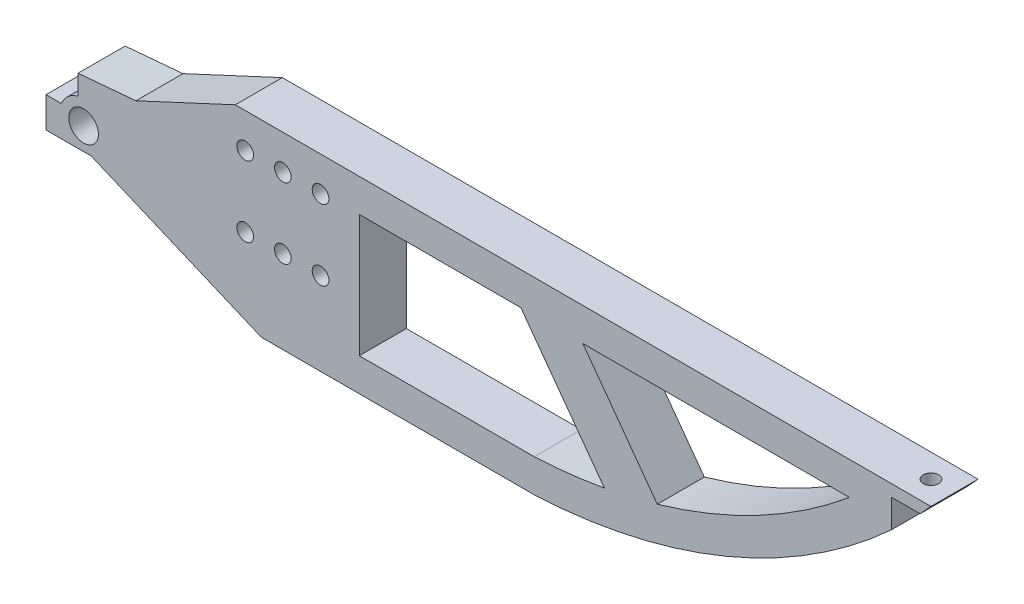
SolidWorks part; units mm, degrees
ref_plane "Front Plane" through (0, 0, 0) normal (0, 0, 1) x (1, 0, 0)
ref_plane "Top Plane" through (0, 0, 0) normal (0, 1, 0) x (1, 0, 0)
ref_plane "Right Plane" through (0, 0, 0) normal (1, 0, 0) x (0, 0, -1)
sketch "Sketch1" plane through (0, 0, 0) normal (0, 0, 1) x (1, 0, 0)
  line L1 (120.65, 25.4) -> (-120.65, 25.4)
  line L2 (120.65, 25.4) -> (120.65, -25.4)
  line L3 (120.65, -25.4) -> (-120.65, -25.4)
  line L4 (-120.65, 25.4) -> (-120.65, -25.4)
  line L5 (120.65, 25.4) -> (-120.65, -25.4) construction
  line L6 (120.65, -25.4) -> (-120.65, 25.4) construction
  point P0 (0, 0)
  dimension "D1" = 241.3
  dimension "D2" = 50.8
extrude "Boss-Extrude1" add sketch "Sketch1" along normal blind 12.7
sketch "Sketch3" plane through (0, 0, 12.7) normal (0, 0, 1) x (1, 0, 0)
  line L0 (0, 0) -> (-120.65, 0) construction
  line L1 (-120.65, 25.4) -> (-120.65, -25.4) construction
  circle A0 centre (-107.95, 0) radius 4
  dimension "D2" = 8
  dimension "D1" = 12.7
extrude "Cut-Extrude1" cut sketch "Sketch3" against normal through all
sketch "Sketch5" plane through (0, 0, 12.7) normal (0, 0, 1) x (1, 0, 0)
  line L0 (-120.65, -25.4) -> (120.65, -25.4) construction
  line L1 (-105.8942, -6.008) -> (-59.9903, -25.4)
  line L2 (-107.95, 6.35) -> (-67.0151, 25.4)
  line L3 (120.65, 25.4) -> (-120.65, 25.4) construction
  line L4 (-67.0151, 25.4) -> (-120.65, 25.4)
  line L5 (-120.65, 25.4) -> (-120.65, -25.4)
  line L6 (-120.65, -25.4) -> (-59.9903, -25.4)
  line L7 (120.65, 25.4) -> (120.65, -25.4)
  line L8 (120.65, -25.4) -> (0, -25.4)
  line L9 (-109.9582, -6.0241) -> (-105.8942, -6.008)
  line L10 (-118.0862, -6.0241) -> (-109.9582, -6.0241)
  line L11 (-118.0862, -6.0241) -> (-118.0862, 2.2309)
  line L12 (-118.0862, 2.2309) -> (-113.8952, 2.2309)
  arc A0 (0, -25.4) -> (120.65, 25.4) centre (6.9175, 126.8429) ccw
  arc A1 (-109.9582, -6.0241) -> (-105.8942, -6.008) centre (-107.95, 0) ccw construction
  arc A2 (-107.95, 6.35) -> (-113.8952, 2.2309) centre (-107.95, 0) ccw
  point P15 (-116.1445, -2.9908)
  line M3 (-120.65, 25.4) -> (-120.65, -25.4)
  line M4 (-120.65, -25.4) -> (120.65, -25.4)
  line M5 (120.65, -25.4) -> (120.65, 25.4)
  line M6 (120.65, 25.4) -> (-120.65, 25.4)
  dimension "D1" = 152.4
  dimension "D2" = 12.7
  dimension "D3" = 45.1505
  dimension "D4" = 45.9039
  dimension "D5" = 8.255
  dimension "D6" = 4.191
  dimension "D7" = 8.128
extrude "Cut-Extrude2" cut sketch "Sketch5" against normal through all contours A2 L2 L1 M6 M3 M4 | A0 L8 M5
sketch "Sketch6" plane through (0, 0, 12.7) normal (0, 0, 1) x (1, 0, 0)
  line L0 (-107.95, 0) -> (91.396, 0) construction
  arc A0 (13.8349, -25.4) -> (120.65, 25.4) centre (6.9175, 126.8429) ccw construction
  circle A1 centre (19.05, 0) radius 3.1347
  dimension "D1" = 127
sketch "Sketch7" plane through (0, 0, 0) normal (0, 0, -1) x (-1, 0, 0)
  line L0 (44.0204, -2.9977) -> (44.0204, 16.0523) construction
  point P3 (44.0204, -2.9977)
  point P4 (44.0204, 16.0523)
  dimension "D1" = 19.05
sketch "Sketch8" plane through (0, 0, 0) normal (0, 0, -1) x (-1, 0, 0)
  point P0 (44.0204, 16.0523)
  point P3 (44.0204, -2.9977)
hole_wizard "#8 Clearance Hole1" positions "Sketch8" profile "Sketch9" hole size "#8" standard "ANSI Inch" end condition through all
sketch "Sketch9" plane through (-44.0204, 16.0523, 0) normal (1, 0, 0) x (0, 1, 0)
  line L0 (0, 0) -> (0, 12.7)
  line L1 (0, 12.7) -> (2.2479, 12.7)
  line L2 (2.2479, 12.7) -> (2.2479, 0)
  line L5 (2.2479, 0) -> (0, 0)
  line L11 (0, -6.35) -> (0, 107.95) construction
  dimension "Thru Hole Dia." = 4.4958
  dimension "Thru Hole Depth" = 12.7
ref_plane "Plane1" through (-114.3, 0, 0) normal (-1, 0, 0) x (0, 0, 1)
sketch "Sketch10" plane through (-114.3, 0, 0) normal (-1, 0, 0) x (0, 0, 1)
  line L0 (0, 0) -> (12.7, 0) construction
  line L1 (12.7, -3.1347) -> (12.7, 3.1347) construction
  circle A0 centre (6.0894, 0) radius 1.905
  dimension "D1" = 3.81
extrude "Cut-Extrude3" cut sketch "Sketch10" against normal blind 5.08
sketch "Sketch11" plane through (0, 0, 12.7) normal (0, 0, 1) x (1, 0, 0)
  line L0 (-93.8249, 12.9234) -> (-109.4459, 12.9234) construction
  line L1 (-107.95, 6.35) -> (-67.0151, 25.4) construction
  line L2 (-109.4459, 12.9234) -> (-109.4459, 5.6538) construction
  line L3 (-93.8249, 12.9234) -> (-109.4459, 5.6538)
  line L4 (-93.8249, 12.9234) -> (-109.4459, 11.5568)
  line L5 (-109.4459, 11.5568) -> (-109.4459, 5.6538)
  circle A1 centre (-107.95, 0) radius 4 construction
  dimension "D1" = 15.621
  dimension "D2" = 5.6538
  dimension "D3" = 175
extrude "Boss-Extrude2" add sketch "Sketch11" against normal up to surface (12.7 mm away) up to face at (-46.2683, 16.0523, 0)
sketch "Sketch12" plane through (0, 0, 12.7) normal (0, 0, 1) x (1, 0, 0)
  line L1 (10.0217, 16.51) -> (-33.5733, 16.51)
  line L24 (-33.5733, 16.51) -> (-33.5733, -16.51)
  line L27 (-33.5733, -16.51) -> (13.63, -16.51)
  line L28 (10.0217, 16.51) -> (32.5572, -14.3581)
  line L29 (26.7339, 16.51) -> (46.8231, -11.0072)
  line L30 (-100.5559, 3.4106) -> (-100.5559, 1.3876)
  line L31 (-100.5559, 1.3876) -> (-58.1896, -16.51)
  line L32 (-58.1896, -16.51) -> (13.63, -16.51)
  line L33 (98.6876, 16.51) -> (-65.0478, 16.51)
  line L34 (-65.0478, 16.51) -> (-91.492, 4.2036)
  line L35 (-91.492, 4.2036) -> (-100.5559, 3.4106)
  line L39 (98.6876, 16.51) -> (26.7339, 16.51)
  arc A0 (46.8231, -11.0072) -> (98.6876, 16.51) centre (6.9175, 126.8429) ccw
  arc A10 (13.63, -16.51) -> (98.6876, 16.51) centre (6.9175, 126.8429) ccw
  arc A11 (13.63, -16.51) -> (32.5572, -14.3581) centre (6.9175, 126.8429) ccw
  dimension "D1" = 8.89
extrude "Cut-Extrude4" cut sketch "Sketch12" against normal through all
sketch "Sketch13" plane through (0, 0, 12.7) normal (0, 0, 1) x (1, 0, 0)
  line L0 (-79.3724, -17.2121) -> (-87.4623, -19.4143)
  line L1 (-105.8942, -6.008) -> (-59.9903, -25.4) construction
  line L2 (-87.4623, -19.4143) -> (-89.1909, -13.0643)
  line L4 (-79.3724, -17.2121) -> (-89.1909, -13.0643)
  circle A0 centre (-107.95, 0) radius 4 construction
  dimension "D1" = 90
  dimension "D2" = 6.35
  dimension "D3" = 22.86
sketch "Sketch14" plane through (0.0221, -5.5891, 0) normal (0.004, -1, 0) x (1, 0.004, 0)
  line L0 (-109.9812, 0) -> (-109.9812, 12.7) construction
  line L2 (-109.9812, 6.35) -> (-105.9171, 6.35) construction
  line L3 (-105.9171, 0) -> (-105.9171, 12.7) construction
  line L4 (-107.9492, 0) -> (-107.9492, 12.7) construction
  line L5 (-109.9812, 0) -> (-105.9171, 0) construction
  line L6 (-109.9812, 12.7) -> (-105.9171, 12.7) construction
  circle A0 centre (-107.9492, 6.35) radius 1.27
  dimension "D1" = 2.54
extrude "Cut-Extrude5" cut sketch "Sketch14" against normal blind 6.35
sketch "Sketch15" plane through (0, 0, 12.7) normal (0, 0, 1) x (1, 0, 0)
  line L0 (117.6404, 22.225) -> (110.0327, 22.225)
  line L1 (120.65, 22.225) -> (57.15, 22.225) construction
  line L2 (110.0327, 22.225) -> (110.0327, 12.8153)
  line L3 (110.0327, 12.8153) -> (117.6404, 12.8153)
  line L4 (117.6404, 12.8153) -> (117.6404, 22.225)
extrude "Cut-Extrude6" cut sketch "Sketch15" against normal through all
sketch "Sketch16" plane through (0, 0, 12.7) normal (0, 0, 1) x (1, 0, 0)
  line L0 (117.7449, 22.225) -> (117.6404, 22.225)
  line L1 (120.65, 22.225) -> (57.15, 22.225) construction
  line L2 (117.6404, 22.225) -> (117.6404, 22.0792)
  line L3 (117.6404, 22.0792) -> (117.7449, 22.0792)
  line L4 (117.7449, 22.0792) -> (117.7449, 22.225)
  dimension "D1" = 0.1046
  dimension "D2" = 0.1458
extrude "Cut-Extrude8" cut sketch "Sketch16" against normal through all contours L4 L0 L2 L3
sketch "Sketch18" plane through (0, 25.4, 0) normal (0, 1, 0) x (1, 0, 0)
  circle A0 centre (114.3, -6.35) radius 2.0828
extrude "Cut-Extrude9" cut sketch "Sketch18" against normal through all contours A0
pattern_linear "LPattern1" count 3 spacing 10.16 along (-1, 0, 0) of "#8 Clearance Hole1"
